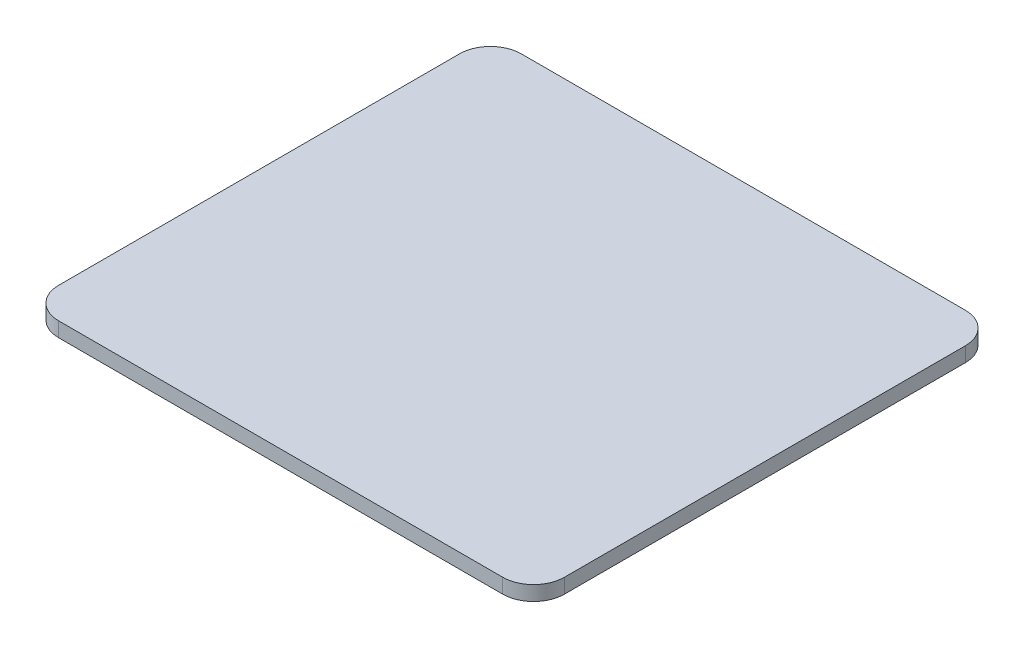
SolidWorks part; units mm, degrees
ref_plane "Front Plane" through (0, 0, 0) normal (0, 0, 1) x (1, 0, 0)
ref_plane "Top Plane" through (0, 0, 0) normal (0, 1, 0) x (1, 0, 0)
ref_plane "Right Plane" through (0, 0, 0) normal (1, 0, 0) x (0, 0, -1)
sketch "Sketch1" plane through (0, 0, 0) normal (0, 1, 0) x (1, 0, 0)
  line L1 (82, -75) -> (-82, -75)
  line L2 (82, -75) -> (82, 75)
  line L3 (82, 75) -> (-82, 75)
  line L4 (-82, -75) -> (-82, 75)
  line L5 (82, -75) -> (-82, 75) construction
  line L6 (82, 75) -> (-82, -75) construction
  point P0 (0, 0)
  dimension "D1" = 164
  dimension "D2" = 150
extrude "Boss-Extrude1" add sketch "Sketch1" along normal blind 4.7625
fillet "Fillet1" radius 10 4 edges at (-82, 2.3813, -75) (82, 2.3813, -75) (82, 2.3813, 75) (-82, 2.3813, 75)
equation "\"C1\"= 169mm"
equation "\"C2\"= 155mm"
equation "\"OFFSET\"= 5mm"
equation "\"D1@Sketch1\"=\"C1\"-\"OFFSET\""
equation "\"D2@Sketch1\"=\"C2\"-\"OFFSET\""
